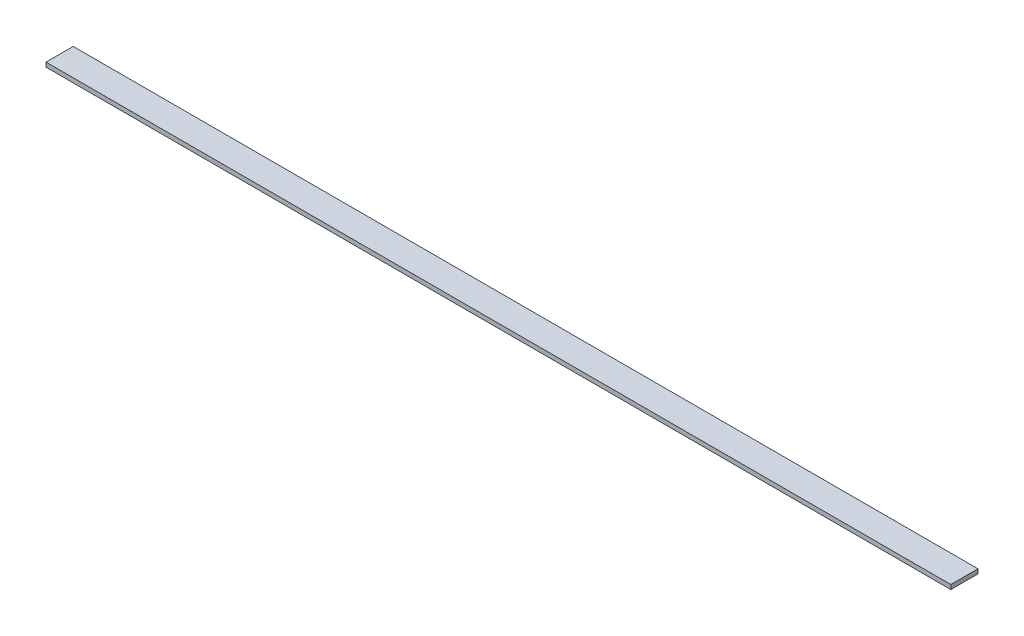
SolidWorks part; units mm, degrees
material "PE High Density"
ref_plane "Front Plane" through (0, 0, 0) normal (0, 0, 1) x (1, 0, 0)
ref_plane "Top Plane" through (0, 0, 0) normal (0, 1, 0) x (1, 0, 0)
ref_plane "Right Plane" through (0, 0, 0) normal (1, 0, 0) x (0, 0, -1)
sketch "Sketch1" plane through (0, 0, 0) normal (0, 1, 0) x (1, 0, 0)
  line L1 (-2175.7624, 532.6736) -> (2261.3001, 532.6736)
  line L2 (-2175.7624, 532.6736) -> (-2175.7624, 399.3236)
  line L3 (-2175.7624, 399.3236) -> (2261.3001, 399.3236)
  line L4 (2261.3001, 532.6736) -> (2261.3001, 399.3236)
  dimension "D1" = 4437.0625
  dimension "D2" = 133.35
extrude "Boss-Extrude1" add sketch "Sketch1" along normal blind 21.59 contours L3 L4 L1 L2
